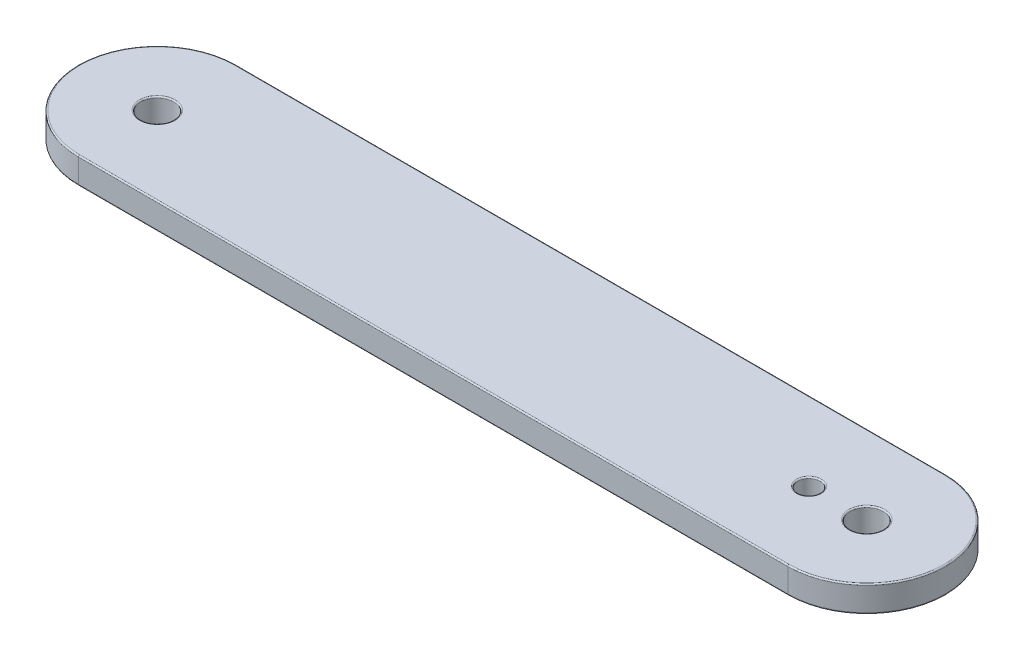
SolidWorks part; units mm, degrees
material "6061 Alloy"
ref_plane "Front Plane" through (0, 0, 0) normal (0, 0, 1) x (1, 0, 0)
ref_plane "Top Plane" through (0, 0, 0) normal (0, 1, 0) x (1, 0, 0)
ref_plane "Right Plane" through (0, 0, 0) normal (1, 0, 0) x (0, 0, -1)
sketch "Sketch1" plane through (0, 0, 0) normal (0, 1, 0) x (1, 0, 0)
  line L0 (0, 0) -> (-171.45, 0) construction
  line L1 (0, -19.05) -> (-171.45, -19.05)
  line L2 (0, 19.05) -> (-171.45, 19.05)
  arc A0 (0, -19.05) -> (0, 19.05) centre (0, 0) ccw
  arc A1 (-171.45, 19.05) -> (-171.45, -19.05) centre (-171.45, 0) ccw
  circle A2 centre (-171.45, 0) radius 4
  circle A3 centre (0, 0) radius 4
  circle A4 centre (-13.97, 0) radius 2.7
  point P3 (-85.725, 0)
  dimension "D3" = 8
  dimension "D4" = 8
  dimension "D5" = 13.97
  dimension "D6" = 5.4
  dimension "D1" = 171.45
  dimension "D2" = 38.1
extrude "Boss-Extrude1" add sketch "Sketch1" along normal blind 6.35
fillet "Fillet1" radius 0.3175 14 edges at (-13.97, 6.35, 2.7) (-171.45, 6.35, 4) (-85.725, 6.35, 19.05) (-190.5, 6.35, 0) (-85.725, 6.35, -19.05) (19.05, 6.35, 0) (0, 6.35, 4) (-13.97, 0, 2.7) (0, 0, 4) (-171.45, 0, 4) (-85.725, 0, -19.05) (-190.5, 0, 0) (-85.725, 0, 19.05) (19.05, 0, 0)
